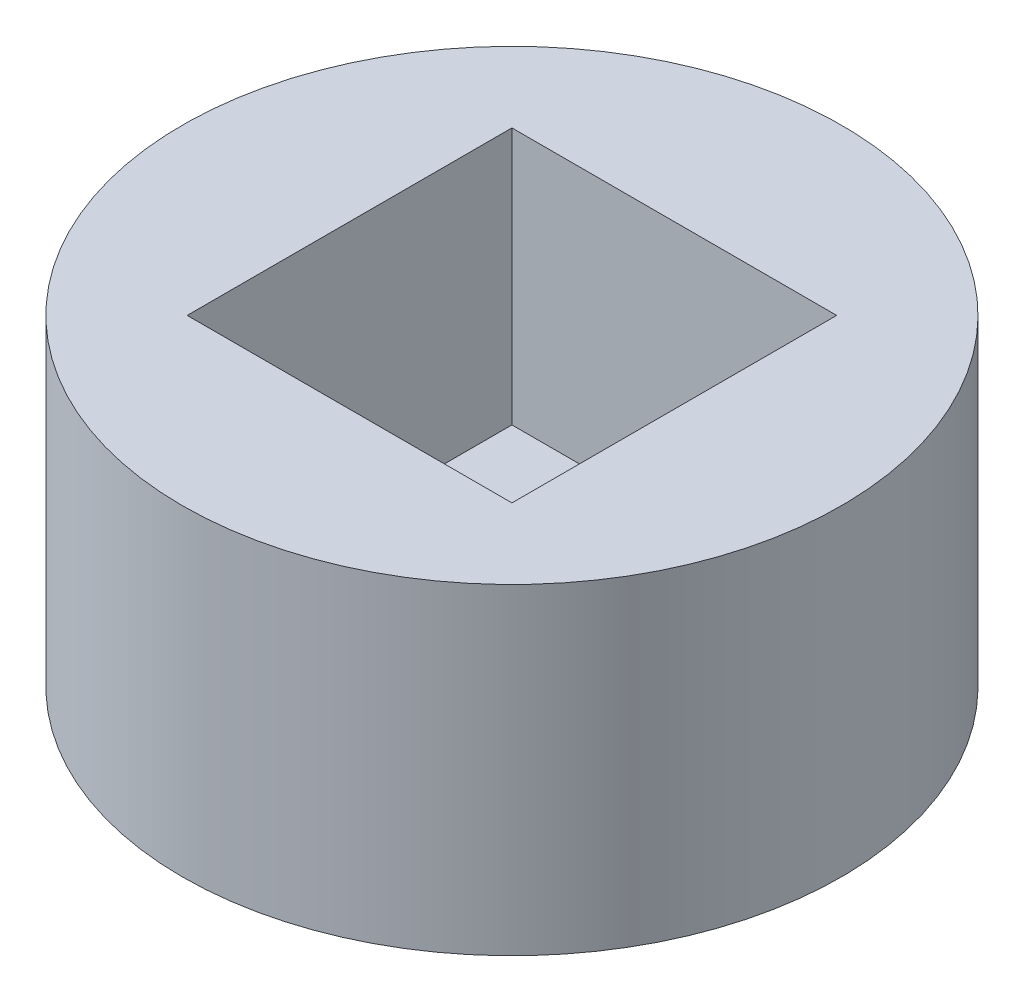
SolidWorks part; units mm, degrees
ref_plane "Front Plane" through (0, 0, 0) normal (0, 0, 1) x (1, 0, 0)
ref_plane "Top Plane" through (0, 0, 0) normal (0, 1, 0) x (1, 0, 0)
ref_plane "Right Plane" through (0, 0, 0) normal (1, 0, 0) x (0, 0, -1)
sketch "Sketch1" plane through (0, 0, 0) normal (0, 1, 0) x (1, 0, 0)
  circle A0 centre (0, 0) radius 26.035
  dimension "D1" = 52.07
extrude "Boss-Extrude1" add sketch "Sketch1" along normal blind 25.4
sketch "Sketch2" plane through (0, 25.4, 0) normal (0, 1, 0) x (1, 0, 0)
  line L1 (-12.827, -12.827) -> (12.827, -12.827)
  line L2 (-12.827, -12.827) -> (-12.827, 12.827)
  line L3 (-12.827, 12.827) -> (12.827, 12.827)
  line L4 (12.827, -12.827) -> (12.827, 12.827)
  line L5 (-12.827, -12.827) -> (12.827, 12.827) construction
  line L6 (-12.827, 12.827) -> (12.827, -12.827) construction
  point P0 (0, 0)
  dimension "D1" = 25.654
  dimension "D2" = 25.654
extrude "Cut-Extrude1" cut sketch "Sketch2" against normal blind 20.32
